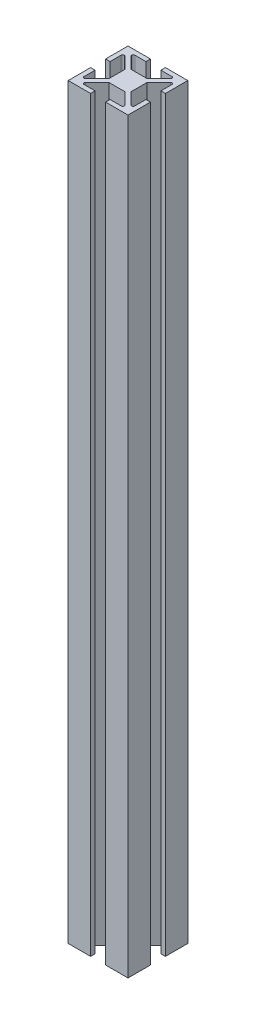
SolidWorks part; units mm, degrees
ref_plane "Plan de face" through (0, 0, 0) normal (0, 0, 1) x (1, 0, 0)
ref_plane "Plan de dessus" through (0, 0, 0) normal (0, 1, 0) x (1, 0, 0)
ref_plane "Plan de droite" through (0, 0, 0) normal (1, 0, 0) x (0, 0, -1)
sketch "Esquisse1" plane through (0, 0, 0) normal (0, 1, 0) x (1, 0, 0)
  line L0 (6.1245, 16.1036) -> (30.6226, 16.1036) construction
  line L6 (-11.5924, 0) -> (12.1076, 0) construction
  line L7 (0, 12.3466) -> (0, -12.7449) construction
  line L12 (-10, -10) -> (10, 10) construction
  line L59 (-10, -2.5) -> (-10, -10)
  line L60 (-10, -2.5) -> (-8.5, -2.5)
  line L69 (-8.5, -2.5) -> (-8.5, -6.2322)
  line L70 (-7.6464, -6.5858) -> (-3.75, -2.6893)
  line L73 (-6.5858, -7.6464) -> (-2.6893, -3.75)
  line L74 (-2.5, -8.5) -> (-6.2322, -8.5)
  line L75 (-2.5, -10) -> (-2.5, -8.5)
  line L76 (-2.5, -10) -> (-10, -10)
  line L77 (-2.5, 10) -> (-2.5, 8.5)
  line L78 (-2.5, 10) -> (-10, 10)
  line L79 (-10, 2.5) -> (-10, 10)
  line L80 (-10, 2.5) -> (-8.5, 2.5)
  line L81 (-8.5, 2.5) -> (-8.5, 6.2322)
  line L82 (-7.6464, 6.5858) -> (-3.75, 2.6893)
  line L83 (-6.5858, 7.6464) -> (-2.6893, 3.75)
  line L84 (-2.5, 8.5) -> (-6.2322, 8.5)
  line L85 (10, 2.5) -> (8.5, 2.5)
  line L86 (10, 2.5) -> (10, 10)
  line L87 (2.5, 10) -> (10, 10)
  line L88 (2.5, 10) -> (2.5, 8.5)
  line L89 (2.5, 8.5) -> (6.2322, 8.5)
  line L90 (6.5858, 7.6464) -> (2.6893, 3.75)
  line L91 (7.6464, 6.5858) -> (3.75, 2.6893)
  line L92 (8.5, 2.5) -> (8.5, 6.2322)
  line L93 (2.5, -10) -> (2.5, -8.5)
  line L94 (2.5, -10) -> (10, -10)
  line L95 (10, -2.5) -> (10, -10)
  line L96 (10, -2.5) -> (8.5, -2.5)
  line L97 (8.5, -2.5) -> (8.5, -6.2322)
  line L98 (7.6464, -6.5858) -> (3.75, -2.6893)
  line L99 (6.5858, -7.6464) -> (2.6893, -3.75)
  line L100 (2.5, -8.5) -> (6.2322, -8.5)
  line L101 (-3.75, 2.6893) -> (-3.75, -2.6893)
  line L102 (-2.6893, -3.75) -> (2.6893, -3.75)
  line L103 (-2.6893, 3.75) -> (2.6893, 3.75)
  line L104 (3.75, 2.6893) -> (3.75, -2.6893)
  arc A0 (-8.5, 6.2322) -> (-7.6464, 6.5858) centre (-8, 6.2322) cw
  arc A1 (-8.5, -6.2322) -> (-7.6464, -6.5858) centre (-8, -6.2322) ccw
  arc A2 (-6.5858, -7.6464) -> (-6.2322, -8.5) centre (-6.2322, -8) ccw
  arc A3 (6.5858, -7.6464) -> (6.2322, -8.5) centre (6.2322, -8) cw
  arc A4 (8.5, -6.2322) -> (7.6464, -6.5858) centre (8, -6.2322) cw
  arc A5 (7.6464, 6.5858) -> (8.5, 6.2322) centre (8, 6.2322) cw
  arc A6 (6.2322, 8.5) -> (6.5858, 7.6464) centre (6.2322, 8) cw
  arc A7 (-6.5858, 7.6464) -> (-6.2322, 8.5) centre (-6.2322, 8) cw
  point P7 (-2.5, -9.25)
  point P8 (2.5, -9.25)
  point P15 (-8.5, -7.4393)
  point P51 (0, 0)
  point P52 (-7.4393, -8.5)
  dimension "D2" = 5
  dimension "D7" = 0.5
  dimension "D1" = 20
  dimension "D3" = 4
  dimension "D4" = 7.5
  dimension "D5" = 1.5
  dimension "D6" = 1.5
extrude "Boss.-Extru.1" add sketch "Esquisse1" along normal blind 250
